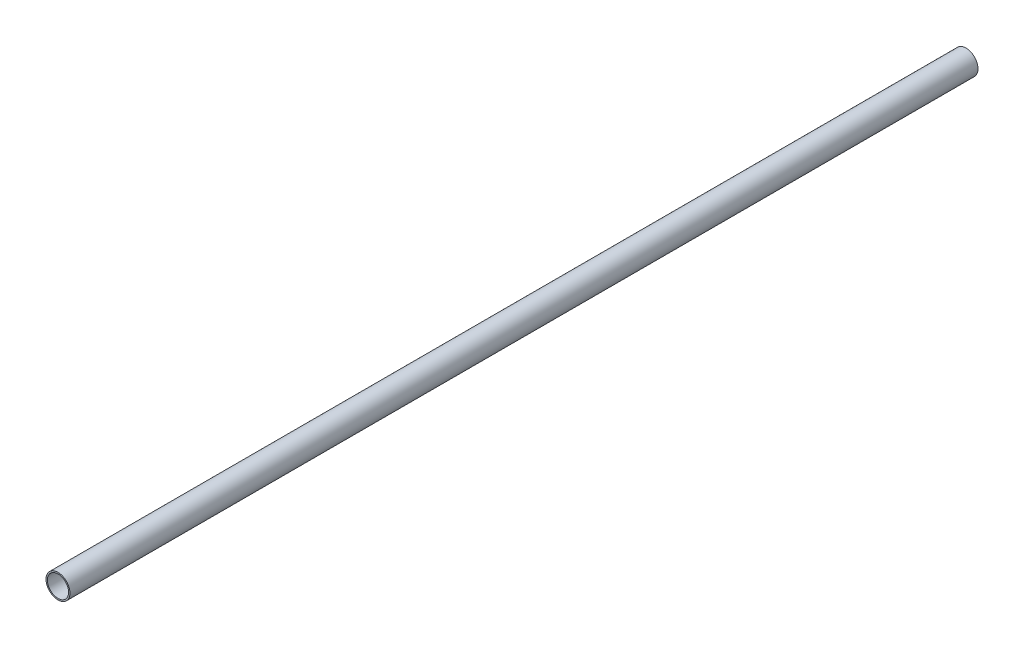
SolidWorks part; units mm, degrees
ref_plane "Front Plane" through (0, 0, 0) normal (0, 0, 1) x (1, 0, 0)
ref_plane "Top Plane" through (0, 0, 0) normal (0, 1, 0) x (1, 0, 0)
ref_plane "Right Plane" through (0, 0, 0) normal (1, 0, 0) x (0, 0, -1)
sketch "Sketch1" plane through (0, 0, 0) normal (0, 0, 1) x (1, 0, 0)
  line L0 (21.3614, 0) -> (24.13, 0) construction
  circle A0 centre (0, 0) radius 24.13 construction
  circle A1 centre (0, 0) radius 21.3614 construction
  dimension "ID" = 42.7228
  dimension "OD" = 48.26
  dimension "Wall Thickness" = 2.7686
sketch "Sketch2" plane through (0, 0, 0) normal (1, 0, 0) x (0, 0, -1)
  line L0 (-914.4, 0) -> (914.4, 0) construction
  line L1 (-860.9965, 24.13) -> (-860.9965, -24.13) construction
  line L2 (860.9965, 24.13) -> (860.9965, -24.13) construction
  point P4 (0, 0)
  point P8 (-860.9965, 0)
  point P11 (860.9965, 0)
  dimension "Length" = 1828.8
  dimension "D1" = 53.4035
  dimension "D2" = 53.4035
  dimension "D3" = 48.26
sketch "Sketch3" plane through (0, 0, 0) normal (0, 0, 1) x (1, 0, 0)
  circle A0 centre (0, 0) radius 24.13
  circle A1 centre (0, 0) radius 24.13 construction
  circle A2 centre (0, 0) radius 21.3614 construction
  circle A3 centre (0, 0) radius 21.3614
extrude "Boss-Extrude1" add sketch "Sketch3" along normal up to vertex (914.4 mm away) and the other way up to vertex (914.4 mm away) up to point (0, 0, 914.4) other way up to point (0, 0, -914.4)
equation "\"D1@Sketch2\"=If(\"ID@Sketch1\">6,5.5,(\"ID@Sketch1\"*1.25))"
equation "\"D2@Sketch2\"=\"D1@Sketch2\""
equation "\"D3@Sketch2\"= \"OD@Sketch1\""
